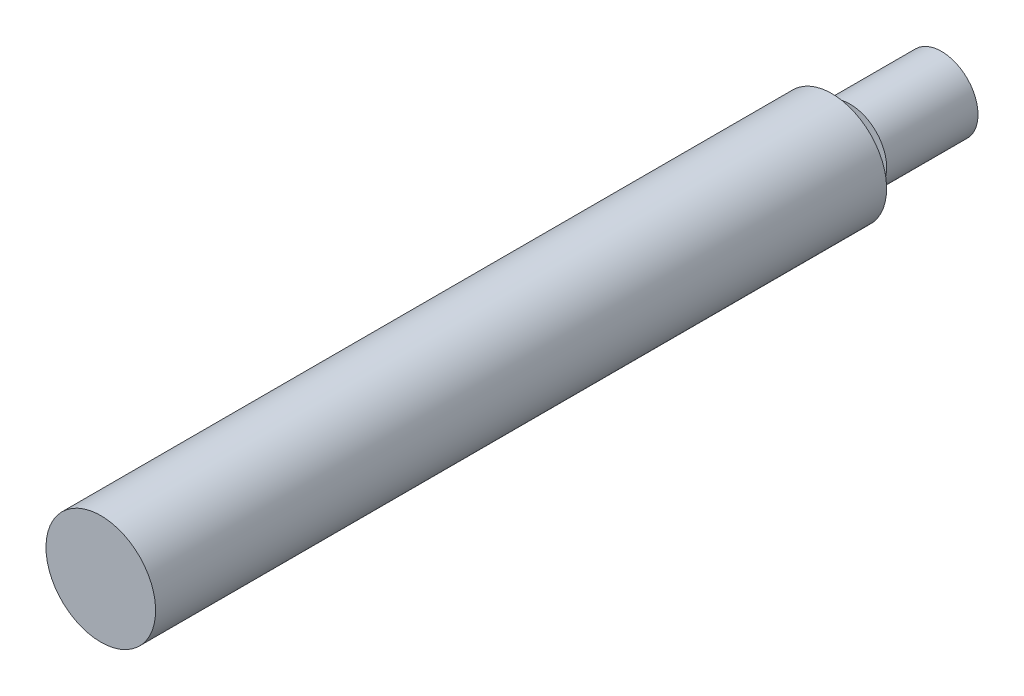
SolidWorks part; units mm, degrees
ref_plane "1" through (0, 0, 0) normal (0, 0, 1) x (1, 0, 0)
ref_plane "2" through (0, 0, 0) normal (0, 1, 0) x (1, 0, 0)
ref_plane "3" through (0, 0, 0) normal (1, 0, 0) x (0, 0, -1)
ref_plane "Front Plane" through (0, 0, 0) normal (0, -1, 0) x (1, 0, 0)
ref_plane "Right Plane" through (0, 0, 0) normal (1, 0, 0) x (0, 1, 0)
ref_plane "Top Plane" through (0, 0, 0) normal (0, 0, 1) x (1, 0, 0)
sketch "Sketch1" plane through (0, 0, 0) normal (0, -1, 0) x (1, 0, 0)
  line L0 (0, 44.6812) -> (0, -7.0401) construction
  line L1 (0, 40) -> (3, 40)
  line L2 (3, 40) -> (3, 0)
  line L3 (3, 0) -> (1.5, 0)
  line L4 (0, -6) -> (2, -6)
  line L5 (2, -6) -> (2, -1)
  line L6 (2, -1) -> (1.5, -1)
  line L7 (1.5, -1) -> (1.5, 0)
  line L8 (0, -6) -> (0, 40)
  point P4 (0, 44.6812)
  dimension "D1" = 6
  dimension "D2" = 6
  dimension "D3" = 4
  dimension "D4" = 40
  dimension "D5" = 1
  dimension "D6" = 3
revolve "Revolve1" add sketch "Sketch1" angle 360 about L0
